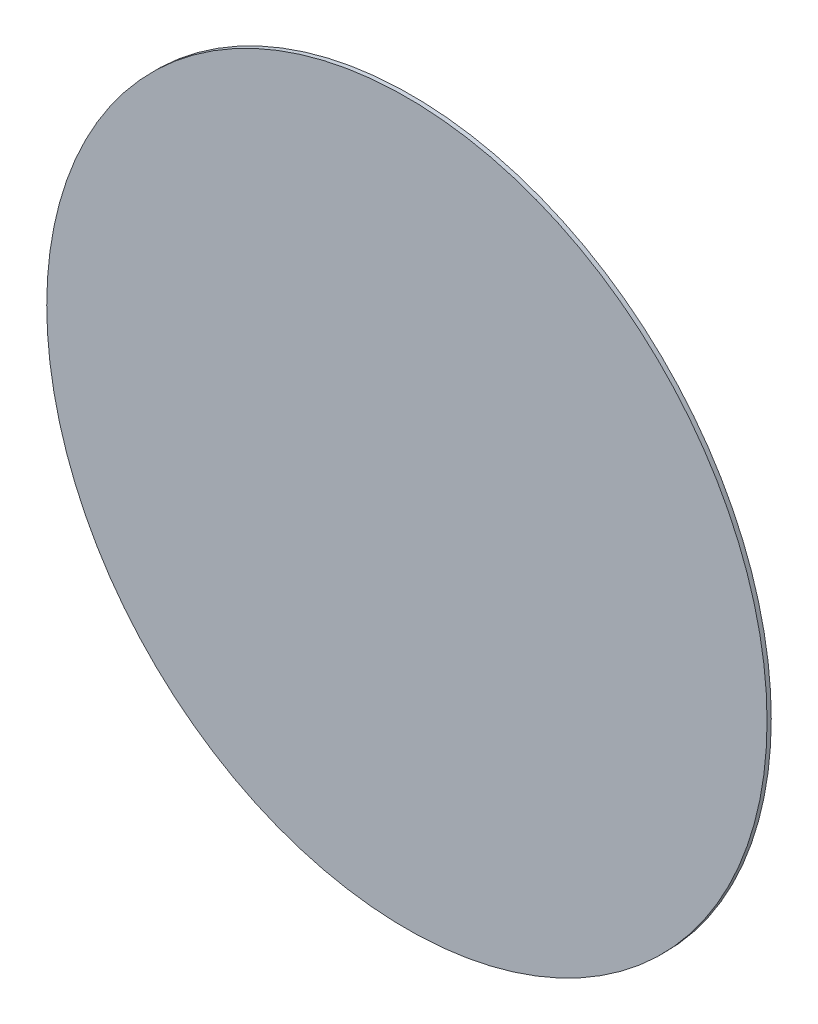
SolidWorks part; units mm, degrees
material "ABS PC"
ref_plane "Front Plane" through (0, 0, 0) normal (0, 0, 1) x (1, 0, 0)
ref_plane "Top Plane" through (0, 0, 0) normal (0, 1, 0) x (1, 0, 0)
ref_plane "Right Plane" through (0, 0, 0) normal (1, 0, 0) x (0, 0, -1)
sketch "Sketch1" plane through (0, 0, 0) normal (0, 0, 1) x (1, 0, 0)
  circle A0 centre (0, 0) radius 2.286 construction
  circle A1 centre (0, 0) radius 15.24
  dimension "D1" = 4.572
  dimension "D2" = 30.48
extrude "Boss-Extrude1" add sketch "Sketch1" along normal blind 0.1778
